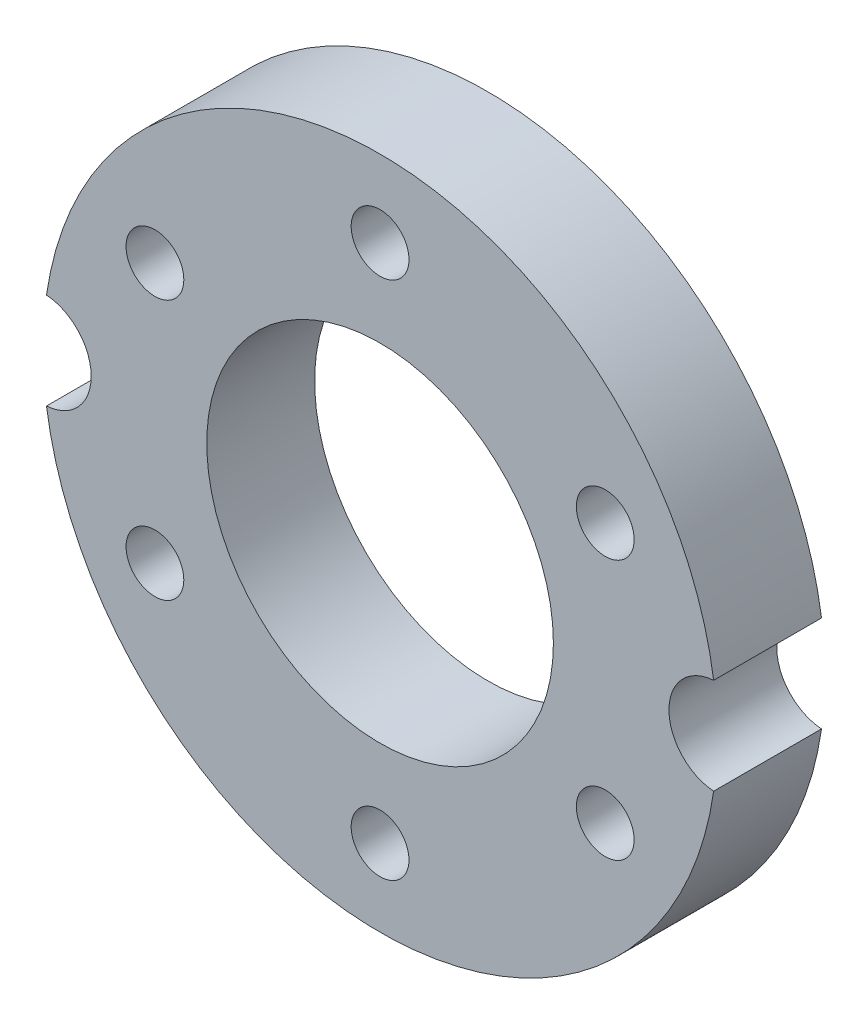
SolidWorks part; units mm, degrees
ref_plane "前视基准面" through (0, 0, 0) normal (0, 0, 1) x (1, 0, 0)
ref_plane "上视基准面" through (0, 0, 0) normal (0, 1, 0) x (1, 0, 0)
ref_plane "右视基准面" through (0, 0, 0) normal (1, 0, 0) x (0, 0, -1)
other "Configuration Table"
sketch "草图1" plane through (0, 0, 0) normal (0, 0, 1) x (1, 0, 0)
  line L0 (0, -1.3726) -> (0, -50001.3726) construction
  circle A0 centre (0, 0) radius 9
  circle A1 centre (0, 0) radius 17.5
  circle A2 centre (0, 13.5) radius 1.5
  circle A3 centre (11.6913, 6.75) radius 1.5
  circle A4 centre (11.6913, -6.75) radius 1.5
  circle A5 centre (0, -13.5) radius 1.5
  circle A6 centre (-11.6913, -6.75) radius 1.5
  circle A7 centre (-11.6913, 6.75) radius 1.5
  circle A8 centre (-17.5, 0) radius 2.5
  circle A9 centre (17.5, 0) radius 2.5
  point P20 (0, 0)
  dimension "D1" = 35
  dimension "D2" = 18
  dimension "D3" = 3
  dimension "D6" = 5
  dimension "D4" = 13.5
  dimension "D5" = 6
extrude "凸台-拉伸1" add sketch "草图1" along normal blind 5.6 contours L0 A1 A8 A5 A0 A2 A7 A6 | A1 L0 A2 A0 A5 A9 A3 A4
